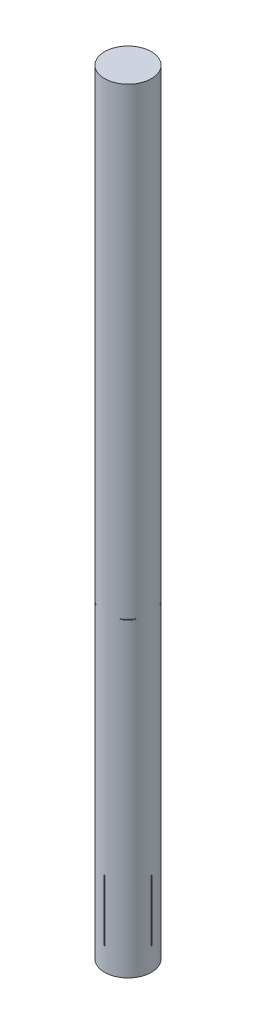
SolidWorks part; units mm, degrees
ref_plane "Front Plane" through (0, 0, 0) normal (0, 0, 1) x (1, 0, 0)
ref_plane "Top Plane" through (0, 0, 0) normal (0, 1, 0) x (1, 0, 0)
ref_plane "Right Plane" through (0, 0, 0) normal (1, 0, 0) x (0, 0, -1)
sketch "Sketch1" plane through (0, 0, 0) normal (0, 1, 0) x (1, 0, 0)
  circle A0 centre (0, 0) radius 77.6224
  circle A2 centre (0, 0) radius 76.2
  dimension "D1" = 152.4
  dimension "D2" = 155.2448
extrude "Boss-Extrude1" add sketch "Sketch1" along normal blind 2565.4
sketch "Sketch2" plane through (0, 0, 0) normal (0, 0, 1) x (1, 0, 0)
  line L0 (0, 0) -> (0, 177.8) construction
  line L1 (-77.6224, 0) -> (77.6224, 0) construction
  line L2 (-2.3813, 279.4) -> (2.3812, 279.4)
  line L3 (-2.3813, 279.4) -> (-2.3813, 76.2)
  line L4 (-2.3813, 76.2) -> (2.3812, 76.2)
  line L5 (2.3812, 279.4) -> (2.3812, 76.2)
  line L6 (-2.3813, 279.4) -> (2.3812, 76.2) construction
  line L7 (-2.3813, 76.2) -> (2.3812, 279.4) construction
  dimension "D1" = 76.2
  dimension "D2" = 203.2
  dimension "D3" = 4.7625
extrude "Cut-Extrude1" cut sketch "Sketch2" against normal through all
pattern_circular "CirPattern1" count 4 over 360 about axis through (0, 0, 0) along (0, 1, 0) of "Cut-Extrude1"
ref_plane "Plane1" through (0, 0, 0) normal (-0.7071, 0, 0.7071) x (0.7071, 0, 0.7071)
sketch "Sketch3" plane through (0, 0, 0) normal (-0.7071, 0, 0.7071) x (0.7071, 0, 0.7071)
  line L0 (0, 0) -> (0, 1029.0175) construction
  line L2 (-19.05, 1030.605) -> (19.05, 1030.605)
  line L3 (-19.05, 1030.605) -> (-19.05, 1027.43)
  line L4 (-19.05, 1027.43) -> (19.05, 1027.43)
  line L5 (19.05, 1030.605) -> (19.05, 1027.43)
  line L6 (-19.05, 1030.605) -> (19.05, 1027.43) construction
  line L7 (-19.05, 1027.43) -> (19.05, 1030.605) construction
  dimension "D1" = 38.1
  dimension "D2" = 1029.0175
  dimension "D3" = 3.175
extrude "Cut-Extrude2" cut sketch "Sketch3" against normal through all
pattern_circular "CirPattern2" count 4 over 360 about axis through (0, 0, 0) along (0, 1, 0) of "Cut-Extrude2"
sketch "Sketch4" plane through (0, 0, 0) normal (0, -1, 0) x (1, 0, 0)
  circle A0 centre (0, 0) radius 76.2
  dimension "D1" = 152.4
extrude "Boss-Extrude2" add sketch "Sketch4" against normal blind 2565.4
